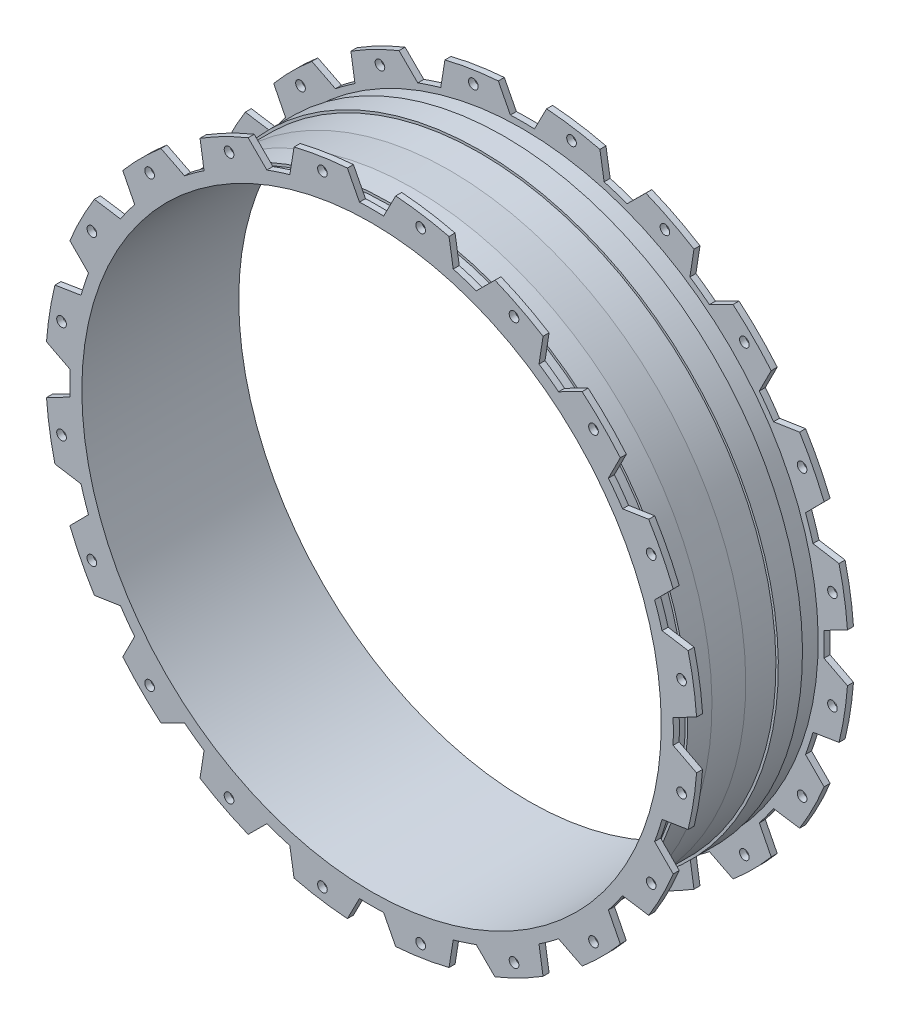
SolidWorks part; units mm, degrees
ref_plane "Front Plane" through (0, 0, 0) normal (0, 0, 1) x (1, 0, 0)
ref_plane "Top Plane" through (0, 0, 0) normal (0, 1, 0) x (1, 0, 0)
ref_plane "Right Plane" through (0, 0, 0) normal (1, 0, 0) x (0, 0, -1)
sketch "Sketch1" plane through (0, 0, 0) normal (1, 0, 0) x (0, 0, -1)
  line L0 (155.8126, 0) -> (-155.8126, 0) construction
  line L1 (65, 240) -> (65, 270)
  line L2 (65, 240) -> (-65, 240)
  line L3 (65, 270) -> (60, 270)
  line L4 (60, 270) -> (60, 245)
  line L5 (60, 245) -> (45, 245)
  line L6 (45, 245) -> (45, 247)
  line L7 (45, 247) -> (25, 247)
  line L8 (25, 247) -> (25, 245)
  line L9 (25, 245) -> (0, 245)
  line L10 (-65, 240) -> (-65, 270)
  line L11 (-65, 270) -> (-60, 270)
  line L12 (-60, 270) -> (-60, 245)
  line L13 (-60, 245) -> (-50, 245)
  line L14 (-50, 245) -> (-50, 247)
  line L15 (-50, 247) -> (-30, 247)
  line L16 (-30, 247) -> (0, 245)
  point P4 (0, 0)
  point P10 (0, 240)
  dimension "D1" = 30
  dimension "D2" = 5
  dimension "D3" = 2
  dimension "D4" = 10
  dimension "D5" = 20
  dimension "D6" = 30
  dimension "D7" = 25
  dimension "D8" = 20
  dimension "D9" = 15
  dimension "D10" = 240
  dimension "D11" = 270
revolve "Revolve1" add sketch "Sketch1" angle 360 about L0
sketch "Sketch2" plane through (0, 0, 65) normal (0, 0, 1) x (1, 0, 0)
  line L0 (0, 270) -> (0, 0) construction
  line L1 (20, 269.2582) -> (10, 249.7999)
  line L2 (-20, 269.2582) -> (-10, 249.7999)
  circle A0 centre (0, 0) radius 270 construction
  circle A1 centre (0, 0) radius 250
  circle A2 centre (0, 0) radius 270
  circle M4 centre (0, 0) radius 270
  dimension "D1" = 500
  dimension "D2" = 20
  dimension "D3" = 10
extrude "Cut-Extrude1" cut sketch "Sketch2" against normal through all contours L0 A2 L2 A1 | L0 A1 L1 M4
pattern_circular "CirPattern1" count 20 over 360 about axis through (0, 0, 0) along (0, 0, 1) of "Cut-Extrude1"
sketch "Sketch3" plane through (0, 0, 65) normal (0, 0, 1) x (1, 0, 0)
  line L0 (42.2373, 266.6759) -> (0, 0) construction
  arc A0 (64.1842, 262.2601) -> (20, 269.2582) centre (0, 0) ccw construction
  circle A1 centre (40.673, 256.799) radius 4
  dimension "D1" = 8
  dimension "D2" = 260
extrude "Cut-Extrude2" cut sketch "Sketch3" against normal through all
pattern_circular "CirPattern2" count 20 over 360 about axis through (0, 0, 0) along (0, 0, 1) of "Cut-Extrude2"
